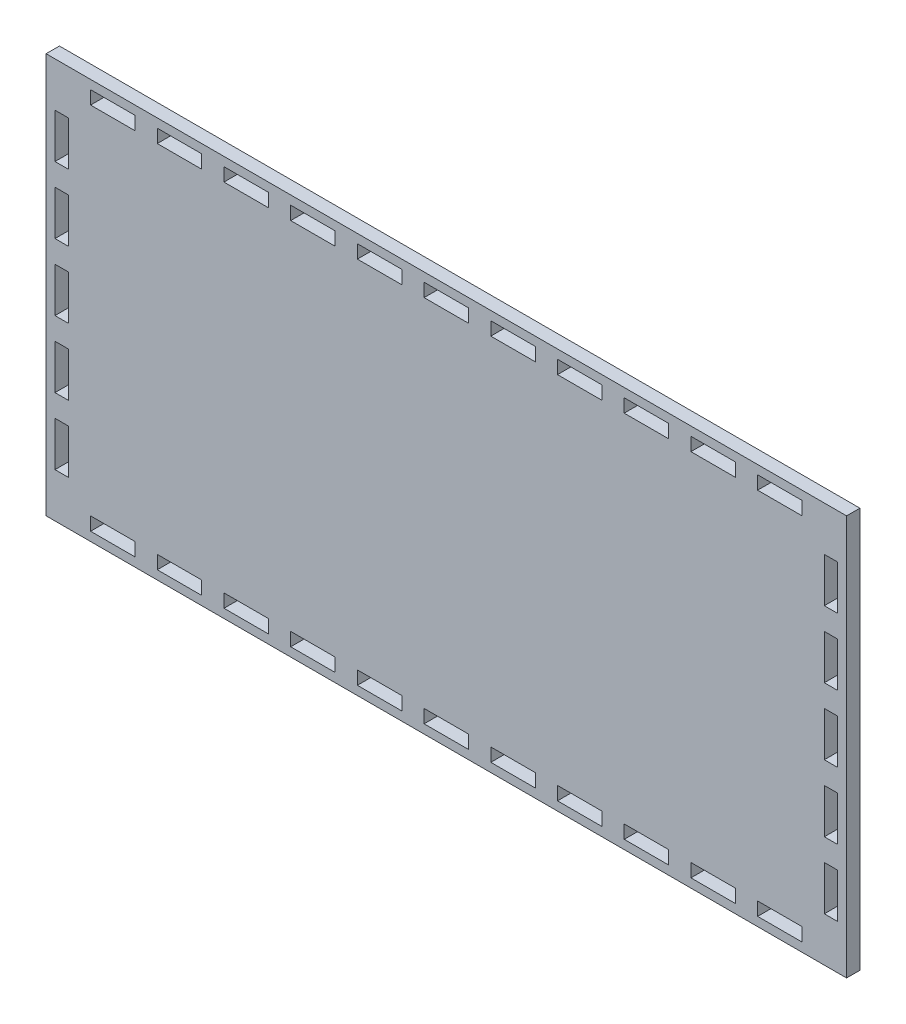
SolidWorks part; units mm, degrees
material "轻木"
ref_plane "前视基准面" through (0, 0, 0) normal (0, 0, 1) x (1, 0, 0)
ref_plane "上视基准面" through (0, 0, 0) normal (0, 1, 0) x (1, 0, 0)
ref_plane "右视基准面" through (0, 0, 0) normal (1, 0, 0) x (0, 0, -1)
sketch "草图1" plane through (0, 0, 0) normal (0, 0, 1) x (1, 0, 0)
  line L4 (-80.0982, 39.7118) -> (-70.0982, 39.7118)
  line L5 (-85.0982, 34.7118) -> (-85.0982, 24.7118)
  line L6 (-85.0982, 34.7118) -> (-88.0982, 34.7118)
  line L7 (-85.0982, 24.7118) -> (-88.0982, 24.7118)
  line L8 (-88.0982, 34.7118) -> (-88.0982, 24.7118)
  line L9 (-85.0982, 19.7118) -> (-88.0982, 19.7118)
  line L10 (-88.0982, 19.7118) -> (-88.0982, 9.7118)
  line L11 (-85.0982, 9.7118) -> (-88.0982, 9.7118)
  line L12 (-85.0982, 4.7118) -> (-88.0982, 4.7118)
  line L13 (-88.0982, 4.7118) -> (-88.0982, -5.2882)
  line L14 (-85.0982, -5.2882) -> (-88.0982, -5.2882)
  line L15 (-85.0982, -10.2882) -> (-88.0982, -10.2882)
  line L16 (-88.0982, -10.2882) -> (-88.0982, -20.2882)
  line L17 (-85.0982, -20.2882) -> (-88.0982, -20.2882)
  line L18 (-85.0982, -25.2882) -> (-88.0982, -25.2882)
  line L19 (-88.0982, -25.2882) -> (-88.0982, -35.2882)
  line L20 (-85.0982, -35.2882) -> (-88.0982, -35.2882)
  line L21 (84.9018, -25.2882) -> (87.9018, -25.2882)
  line L22 (87.9018, -25.2882) -> (87.9018, -35.2882)
  line L23 (84.9018, -35.2882) -> (87.9018, -35.2882)
  line L24 (84.9018, -10.2882) -> (87.9018, -10.2882)
  line L25 (87.9018, -10.2882) -> (87.9018, -20.2882)
  line L26 (84.9018, -20.2882) -> (87.9018, -20.2882)
  line L27 (84.9018, 4.7118) -> (87.9018, 4.7118)
  line L28 (87.9018, 4.7118) -> (87.9018, -5.2882)
  line L29 (84.9018, -5.2882) -> (87.9018, -5.2882)
  line L30 (84.9018, 19.7118) -> (87.9018, 19.7118)
  line L31 (87.9018, 19.7118) -> (87.9018, 9.7118)
  line L32 (84.9018, 9.7118) -> (87.9018, 9.7118)
  line L33 (84.9018, 24.7118) -> (87.9018, 24.7118)
  line L34 (84.9018, 34.7118) -> (87.9018, 34.7118)
  line L35 (87.9018, 34.7118) -> (87.9018, 24.7118)
  line L36 (-65.0982, 39.7118) -> (-65.0982, 42.7118)
  line L37 (-80.0982, 39.7118) -> (-80.0982, 42.7118)
  line L38 (-80.0982, 42.7118) -> (-70.0982, 42.7118)
  line L39 (-70.0982, 39.7118) -> (-70.0982, 42.7118)
  line L40 (-55.0982, 39.7118) -> (-55.0982, 42.7118)
  line L41 (-65.0982, 42.7118) -> (-55.0982, 42.7118)
  line L42 (-50.0982, 39.7118) -> (-50.0982, 42.7118)
  line L43 (-40.0982, 39.7118) -> (-40.0982, 42.7118)
  line L44 (-50.0982, 42.7118) -> (-40.0982, 42.7118)
  line L45 (-35.0982, 39.7118) -> (-35.0982, 42.7118)
  line L46 (-25.0982, 39.7118) -> (-25.0982, 42.7118)
  line L47 (-35.0982, 42.7118) -> (-25.0982, 42.7118)
  line L48 (-20.0982, 39.7118) -> (-20.0982, 42.7118)
  line L49 (-10.0982, 39.7118) -> (-10.0982, 42.7118)
  line L50 (-20.0982, 42.7118) -> (-10.0982, 42.7118)
  line L51 (-5.0982, 39.7118) -> (-5.0982, 42.7118)
  line L52 (4.9018, 39.7118) -> (4.9018, 42.7118)
  line L53 (-5.0982, 42.7118) -> (4.9018, 42.7118)
  line L54 (9.9018, 39.7118) -> (9.9018, 42.7118)
  line L55 (19.9018, 39.7118) -> (19.9018, 42.7118)
  line L56 (9.9018, 42.7118) -> (19.9018, 42.7118)
  line L57 (24.9018, 39.7118) -> (24.9018, 42.7118)
  line L58 (34.9018, 39.7118) -> (34.9018, 42.7118)
  line L59 (24.9018, 42.7118) -> (34.9018, 42.7118)
  line L60 (39.9018, 39.7118) -> (39.9018, 42.7118)
  line L61 (49.9018, 39.7118) -> (49.9018, 42.7118)
  line L62 (39.9018, 42.7118) -> (49.9018, 42.7118)
  line L63 (54.9018, 39.7118) -> (54.9018, 42.7118)
  line L64 (64.9018, 39.7118) -> (64.9018, 42.7118)
  line L65 (54.9018, 42.7118) -> (64.9018, 42.7118)
  line L66 (69.9018, 39.7118) -> (69.9018, 42.7118)
  line L67 (79.9018, 39.7118) -> (79.9018, 42.7118)
  line L68 (69.9018, 42.7118) -> (79.9018, 42.7118)
  line L69 (79.9018, -40.2882) -> (79.9018, -43.2882)
  line L70 (69.9018, -43.2882) -> (79.9018, -43.2882)
  line L71 (69.9018, -40.2882) -> (69.9018, -43.2882)
  line L72 (64.9018, -40.2882) -> (64.9018, -43.2882)
  line L73 (54.9018, -43.2882) -> (64.9018, -43.2882)
  line L74 (54.9018, -40.2882) -> (54.9018, -43.2882)
  line L75 (49.9018, -40.2882) -> (49.9018, -43.2882)
  line L76 (39.9018, -43.2882) -> (49.9018, -43.2882)
  line L77 (39.9018, -40.2882) -> (39.9018, -43.2882)
  line L78 (34.9018, -40.2882) -> (34.9018, -43.2882)
  line L79 (24.9018, -43.2882) -> (34.9018, -43.2882)
  line L80 (24.9018, -40.2882) -> (24.9018, -43.2882)
  line L81 (19.9018, -40.2882) -> (19.9018, -43.2882)
  line L82 (9.9018, -43.2882) -> (19.9018, -43.2882)
  line L83 (9.9018, -40.2882) -> (9.9018, -43.2882)
  line L84 (4.9018, -40.2882) -> (4.9018, -43.2882)
  line L85 (-5.0982, -43.2882) -> (4.9018, -43.2882)
  line L86 (-5.0982, -40.2882) -> (-5.0982, -43.2882)
  line L87 (-10.0982, -40.2882) -> (-10.0982, -43.2882)
  line L88 (-20.0982, -43.2882) -> (-10.0982, -43.2882)
  line L89 (-20.0982, -40.2882) -> (-20.0982, -43.2882)
  line L90 (-25.0982, -40.2882) -> (-25.0982, -43.2882)
  line L91 (-35.0982, -43.2882) -> (-25.0982, -43.2882)
  line L92 (-35.0982, -40.2882) -> (-35.0982, -43.2882)
  line L93 (-40.0982, -40.2882) -> (-40.0982, -43.2882)
  line L94 (-50.0982, -43.2882) -> (-40.0982, -43.2882)
  line L95 (-50.0982, -40.2882) -> (-50.0982, -43.2882)
  line L96 (-55.0982, -40.2882) -> (-55.0982, -43.2882)
  line L97 (-65.0982, -43.2882) -> (-55.0982, -43.2882)
  line L98 (-65.0982, -40.2882) -> (-65.0982, -43.2882)
  line L99 (-80.0982, -43.2882) -> (-70.0982, -43.2882)
  line L100 (-70.0982, -40.2882) -> (-70.0982, -43.2882)
  line L101 (-80.0982, -40.2882) -> (-80.0982, -43.2882)
  line L134 (79.9018, -40.2882) -> (89.9018, -45.2882) construction
  line L135 (-90.0982, 44.7118) -> (89.9018, 44.7118)
  line L136 (-90.0982, 44.7118) -> (-90.0982, -45.2882)
  line L137 (-90.0982, -45.2882) -> (89.9018, -45.2882)
  line L138 (89.9018, 44.7118) -> (89.9018, -45.2882)
  line L139 (-90.0982, 44.7118) -> (-80.0982, 39.7118) construction
  line L140 (-90.0982, -45.2882) -> (-80.0982, -40.2882) construction
  line L141 (-65.0982, 39.7118) -> (-55.0982, 39.7118)
  line L142 (-50.0982, 39.7118) -> (-40.0982, 39.7118)
  line L143 (-35.0982, 39.7118) -> (-25.0982, 39.7118)
  line L144 (-20.0982, 39.7118) -> (-10.0982, 39.7118)
  line L145 (-5.0982, 39.7118) -> (4.9018, 39.7118)
  line L146 (9.9018, 39.7118) -> (19.9018, 39.7118)
  line L147 (24.9018, 39.7118) -> (34.9018, 39.7118)
  line L148 (39.9018, 39.7118) -> (49.9018, 39.7118)
  line L149 (54.9018, 39.7118) -> (64.9018, 39.7118)
  line L150 (69.9018, 39.7118) -> (79.9018, 39.7118)
  line L151 (-85.0982, 19.7118) -> (-85.0982, 9.7118)
  line L152 (-85.0982, 4.7118) -> (-85.0982, -5.2882)
  line L153 (-85.0982, -10.2882) -> (-85.0982, -20.2882)
  line L154 (-85.0982, -25.2882) -> (-85.0982, -35.2882)
  line L156 (-80.0982, -40.2882) -> (-70.0982, -40.2882)
  line L157 (-65.0982, -40.2882) -> (-55.0982, -40.2882)
  line L158 (-50.0982, -40.2882) -> (-40.0982, -40.2882)
  line L159 (-35.0982, -40.2882) -> (-25.0982, -40.2882)
  line L160 (-20.0982, -40.2882) -> (-10.0982, -40.2882)
  line L161 (-5.0982, -40.2882) -> (4.9018, -40.2882)
  line L162 (9.9018, -40.2882) -> (19.9018, -40.2882)
  line L163 (24.9018, -40.2882) -> (34.9018, -40.2882)
  line L164 (39.9018, -40.2882) -> (49.9018, -40.2882)
  line L165 (54.9018, -40.2882) -> (64.9018, -40.2882)
  line L166 (69.9018, -40.2882) -> (79.9018, -40.2882)
  line L167 (84.9018, 34.7118) -> (84.9018, 24.7118)
  line L168 (84.9018, 19.7118) -> (84.9018, 9.7118)
  line L169 (84.9018, 4.7118) -> (84.9018, -5.2882)
  line L170 (84.9018, -10.2882) -> (84.9018, -20.2882)
  line L171 (84.9018, -25.2882) -> (84.9018, -35.2882)
  point P0 (-0.0982, -0.2882)
  point P133 (-0.0982, -0.2882)
  dimension "D2" = 11
  dimension "D3" = 3
  dimension "D4" = 10
  dimension "D5" = 5
  dimension "D6" = 3
  dimension "D7" = 10
  dimension "D8" = 11
  dimension "D9" = 90
  dimension "D10" = 180
  dimension "D11" = 5
extrude "凸台-拉伸1" add sketch "草图1" along normal blind 3
